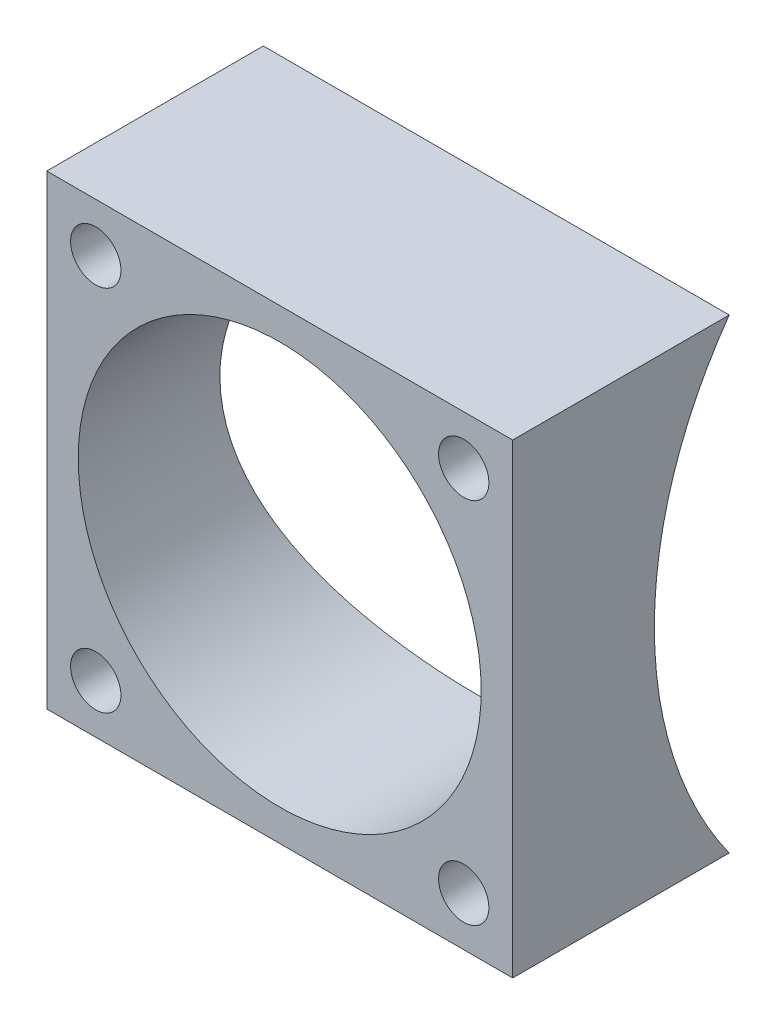
SolidWorks part; units mm, degrees
ref_plane "Front Plane" through (0, 0, 0) normal (0, 0, 1) x (1, 0, 0)
ref_plane "Top Plane" through (0, 0, 0) normal (0, 1, 0) x (1, 0, 0)
ref_plane "Right Plane" through (0, 0, 0) normal (1, 0, 0) x (0, 0, -1)
sketch "Sketch1" plane through (0, 0, 0) normal (0, 0, 1) x (1, 0, 0)
  line L1 (-18.5, 18.5) -> (18.5, 18.5)
  line L2 (-18.5, 18.5) -> (-18.5, -18.5)
  line L3 (-18.5, -18.5) -> (18.5, -18.5)
  line L4 (18.5, 18.5) -> (18.5, -18.5)
  line L5 (-18.5, 18.5) -> (18.5, -18.5) construction
  line L6 (-18.5, -18.5) -> (18.5, 18.5) construction
  point P0 (0, 0)
  dimension "D1" = 37
  dimension "D2" = 37
extrude "Boss-Extrude1" add sketch "Sketch1" along normal blind 43
sketch "Sketch2" plane through (0, 0, 0) normal (1, 0, 0) x (0, 0, -1)
  circle A0 centre (0, 0) radius 31.75
  dimension "D1" = 63.5
extrude "Cut-Extrude1" cut sketch "Sketch2" against normal blind 20 and the other way blind 20
sketch "Sketch5" plane through (0, 0, 0) normal (0, 0, 1) x (1, 0, 0)
  circle A0 centre (0, 0) radius 16
  dimension "D1" = 32
extrude "Cut-Extrude2" cut sketch "Sketch5" along normal through all
sketch "Sketch6" plane through (0, 0, 43) normal (0, 0, 1) x (1, 0, 0)
  line L0 (-18.5, 18.5) -> (18.5, -18.5) construction
  line L1 (18.5, -18.5) -> (-18.5, -18.5) construction
  line L2 (-18.5, -18.5) -> (18.5, 18.5) construction
  circle A1 centre (-14.6109, -14.6109) radius 2
  circle A2 centre (14.6109, -14.6109) radius 2
  circle A3 centre (14.6109, 14.6109) radius 2
  circle A4 centre (-14.6109, 14.6109) radius 2
  point P4 (-14.6109, 14.6109)
  point P9 (14.6109, 14.6109)
  point P10 (-14.6109, -14.6109)
  point P11 (14.6109, -14.6109)
  dimension "D5" = 4
  dimension "D6" = 4
  dimension "D7" = 4
  dimension "D8" = 4
  dimension "D1" = 5.5
  dimension "D2" = 5.5
  dimension "D3" = 5.5
  dimension "D4" = 5.5
extrude "Cut-Extrude3" cut sketch "Sketch6" against normal through all
